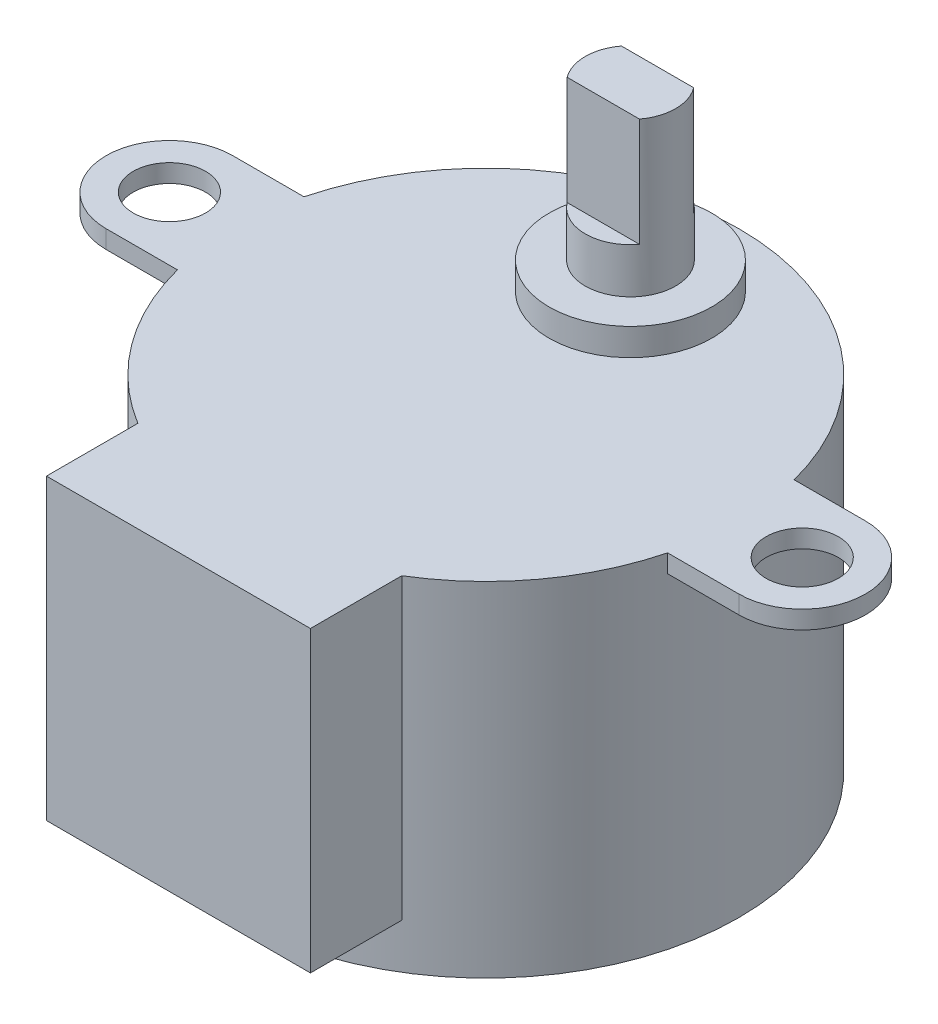
SolidWorks part; units mm, degrees
ref_plane "Спереди" through (0, 0, 0) normal (0, 0, 1) x (1, 0, 0)
ref_plane "Сверху" through (0, 0, 0) normal (0, 1, 0) x (1, 0, 0)
ref_plane "Справа" through (0, 0, 0) normal (1, 0, 0) x (0, 0, -1)
sketch "Эскиз1" plane through (0, 0, 0) normal (0, 1, 0) x (1, 0, 0)
  circle A0 centre (0, 0) radius 14
  dimension "D1" = 28
extrude "Бобышка-Вытянуть1" add sketch "Эскиз1" along normal blind 19
sketch "Эскиз2" plane through (0, 19, 0) normal (0, 1, 0) x (1, 0, 0)
  line L0 (0, 0) -> (0, 50000) construction
  circle A0 centre (0, 8) radius 4.5
  dimension "D2" = 9
  dimension "D1" = 8
extrude "Бобышка-Вытянуть2" add sketch "Эскиз2" along normal blind 1.5
sketch "Эскиз3" plane through (0, 20.5, 0) normal (0, 1, 0) x (1, 0, 0)
  circle A0 centre (0, 8) radius 2.5
  dimension "D1" = 5
extrude "Бобышка-Вытянуть3" add sketch "Эскиз3" along normal blind 8.5
sketch "Эскиз4" plane through (0, 29, 0) normal (0, 1, 0) x (1, 0, 0)
  line L0 (-2, 9.5) -> (2, 9.5)
  line L1 (-2, 6.5) -> (2, 6.5)
  circle A0 centre (0, 8) radius 2.5 construction
  arc A1 (-2, 6.5) -> (2, 6.5) centre (0, 8) ccw
  arc A2 (2, 9.5) -> (-2, 9.5) centre (0, 8) ccw
  dimension "D1" = 3
extrude "Вырез-Вытянуть1" cut sketch "Эскиз4" against normal blind 6
sketch "Эскиз5" plane through (0, 19, 0) normal (0, 1, 0) x (1, 0, 0)
  line L0 (0, 0) -> (-50000, 0) construction
  line L1 (0, 0) -> (0, -50000) construction
  line L2 (-17.5, 3.5) -> (-13.5554, 3.5)
  line L3 (-17.5, -3.5) -> (-13.5554, -3.5)
  line L4 (17.5, 3.5) -> (13.5554, 3.5)
  line L5 (17.5, -3.5) -> (13.5554, -3.5)
  circle A0 centre (-17.5, 0) radius 2
  arc A1 (-17.5, 3.5) -> (-17.5, -3.5) centre (-17.5, 0) ccw
  circle A2 centre (0, 0) radius 14 construction
  arc A3 (-13.5554, 3.5) -> (-13.5554, -3.5) centre (0, 0) ccw
  circle A4 centre (17.5, 0) radius 2
  arc A5 (13.5554, 3.5) -> (13.5554, -3.5) centre (0, 0) cw
  arc A6 (17.5, 3.5) -> (17.5, -3.5) centre (17.5, 0) cw
  dimension "D1" = 4
  dimension "D3" = 7
  dimension "D2" = 35
extrude "Бобышка-Вытянуть4" add sketch "Эскиз5" against normal blind 1
sketch "Эскиз6" plane through (0, 19, 0) normal (0, 1, 0) x (1, 0, 0)
  line L0 (0, 0) -> (0, -50000) construction
  line L2 (7.3, -17) -> (-7.3, -17)
  line L3 (7.3, -17) -> (7.3, -11.9461)
  line L5 (-7.3, -17) -> (-7.3, -11.9461)
  line L6 (7.3, -17) -> (-7.3, -11.9461) construction
  line L7 (7.3, -11.9461) -> (-7.3, -17) construction
  arc A0 (-13.5554, -3.5) -> (13.5554, -3.5) centre (0, 0) ccw construction
  arc A1 (-7.3, -11.9461) -> (7.3, -11.9461) centre (0, 0) ccw
  point P3 (0, -14.4731)
  dimension "D1" = 17
  dimension "D2" = 14.6
extrude "Бобышка-Вытянуть5" add sketch "Эскиз6" against normal blind 16.5
